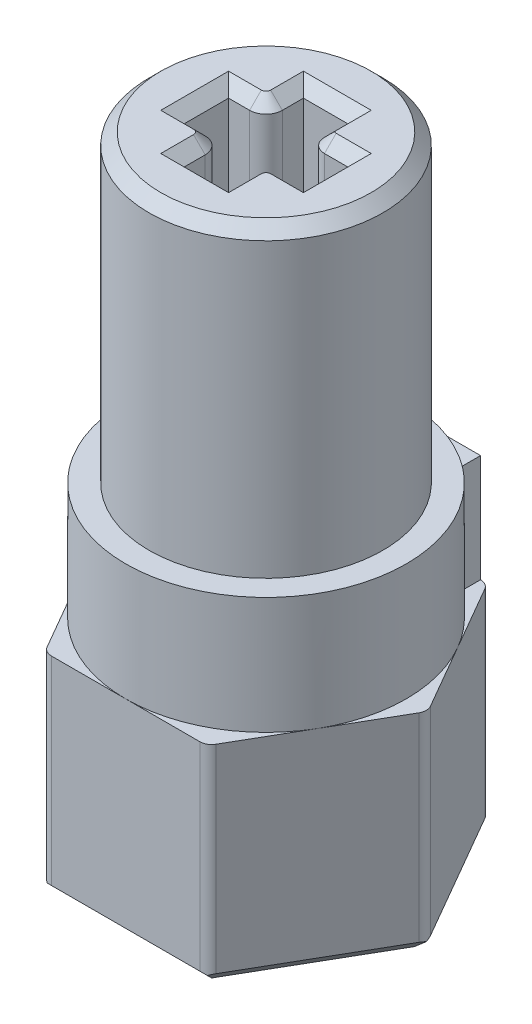
SolidWorks part; units mm, degrees
ref_plane "正面" through (0, 0, 0) normal (0, 0, 1) x (1, 0, 0)
ref_plane "平面" through (0, 0, 0) normal (0, 1, 0) x (1, 0, 0)
ref_plane "右側面" through (0, 0, 0) normal (1, 0, 0) x (0, 0, -1)
sketch "ｽｹｯﾁ1" plane through (0, 0, 0) normal (0, 1, 0) x (1, 0, 0)
  line L1 (-2.55, 0.95) -> (2.55, 0.95)
  line L2 (-2.55, 0.95) -> (-2.55, -0.95)
  line L3 (-2.55, -0.95) -> (2.55, -0.95)
  line L4 (2.55, 0.95) -> (2.55, -0.95)
  line L5 (-2.55, 0.95) -> (2.55, -0.95) construction
  line L6 (-2.55, -0.95) -> (2.55, 0.95) construction
  line L7 (-0.95, 2.55) -> (0.95, 2.55)
  line L8 (-0.95, 2.55) -> (-0.95, -2.55)
  line L9 (-0.95, -2.55) -> (0.95, -2.55)
  line L10 (0.95, 2.55) -> (0.95, -2.55)
  line L11 (-0.95, 2.55) -> (0.95, -2.55) construction
  line L12 (-0.95, -2.55) -> (0.95, 2.55) construction
  circle A0 centre (0, 0) radius 6
  dimension "D1" = 12
  dimension "D2" = 1.9
  dimension "D3" = 5.1
extrude "ﾎﾞｽ - 押し出し4" add sketch "ｽｹｯﾁ1" along normal blind 18 contours A0 | L8 L7 L10 L9 | L2 L1 L4 L3
fillet "ﾌｨﾚｯﾄ1" radius 0.6 1 edges at (0.95, 9, -0.95)
fillet "ﾌｨﾚｯﾄ6" radius 0.7 3 edges at (-0.95, 9, 0.95) (-0.95, 9, -0.95) (0.95, 9, 0.95)
sketch "ｽｹｯﾁ2" plane through (0, 0, 0) normal (0, -1, 0) x (1, 0, 0)
  line L1 (6.9282, 0) -> (3.4641, 6)
  line L2 (3.4641, 6) -> (-3.4641, 6)
  line L3 (-3.4641, 6) -> (-6.9282, 0)
  line L4 (-6.9282, 0) -> (-3.4641, -6)
  line L5 (-3.4641, -6) -> (3.4641, -6)
  line L6 (3.4641, -6) -> (6.9282, 0)
  circle A0 centre (0, 0) radius 6 construction
extrude "ﾎﾞｽ - 押し出し5" add sketch "ｽｹｯﾁ2" along normal blind 9
sketch "ｽｹｯﾁ3" plane through (0, -9, 0) normal (0, -1, 0) x (1, 0, 0)
  circle A0 centre (0, 0) radius 2.55
  dimension "D1" = 5.1
extrude "ｶｯﾄ - 押し出し1" cut sketch "ｽｹｯﾁ3" against normal blind 6 contours A0
chamfer "面取り1" distance 0.5 angle 45 7 edges at (0, -9, -6) (-5.1962, -9, -3) (-5.1962, -9, 3) (0, -9, 6) (5.1962, -9, 3) (5.1962, -9, -3) (0, -9, -2.55)
fillet "ﾌｨﾚｯﾄ4" radius 0.5 1 edges at (-3.4641, -4.25, 6)
fillet "ﾌｨﾚｯﾄ5" radius 0.5 5 edges at (-6.9282, -4.25, 0) (-3.4641, -4.25, -6) (3.4641, -4.25, -6) (6.9282, -4.25, 0) (3.4641, -4.25, 6)
sketch "ｽｹｯﾁ4" plane through (0, 0, -2.55) normal (0, 0, 1) x (1, 0, 0)
  line L6 (-3.1538, 0) -> (3.1754, 0)
  line L7 (-3.1538, 0) -> (-3.1538, 4.6)
  line L8 (-3.1538, 4.6) -> (3.1754, 4.6)
  line L9 (3.1754, 0) -> (3.1754, 4.6)
  dimension "D1" = 4.6
extrude "ﾎﾞｽ - 押し出し6" add sketch "ｽｹｯﾁ4" against normal up to surface (3.45 mm away) up to face at (0, -3.4, -6)
sketch "ｽｹｯﾁ5" plane through (0, 0, -6) normal (0, 0, -1) x (-1, 0, 0)
  circle A0 centre (0, 2) radius 1.2
  dimension "D1" = 2.4
  dimension "D2" = 2
extrude "ｶｯﾄ - 押し出し2" cut sketch "ｽｹｯﾁ5" against normal up to surface (3.45 mm away) up to face at (0, 9, -2.55)
sketch "ｽｹｯﾁ7" plane through (0, 18, 0) normal (0, 1, 0) x (1, 0, 0)
  circle A0 centre (0, 0) radius 5
  circle M2 centre (0, 0) radius 6
  dimension "D1" = 10
extrude "ｶｯﾄ - 押し出し4" cut sketch "ｽｹｯﾁ7" against normal blind 13 contours A0 M2
chamfer "面取り2" distance 0.5 angle 45 17 edges at (0, 18, 5) (0, 18, 2.55) (0.95, 18, 2.1) (1.155, 18, 1.155) (2.1, 18, 0.95) (2.55, 18, 0) (2.05, 18, -0.95) (1.1257, 18, -1.1257) (0.95, 18, -2.05) (0, 18, -2.55) (-0.95, 18, -2.1) (-1.155, 18, -1.155) (-2.1, 18, -0.95) (-2.55, 18, 0) (-2.1, 18, 0.95) (-1.155, 18, 1.155) (-0.95, 18, 2.1)
